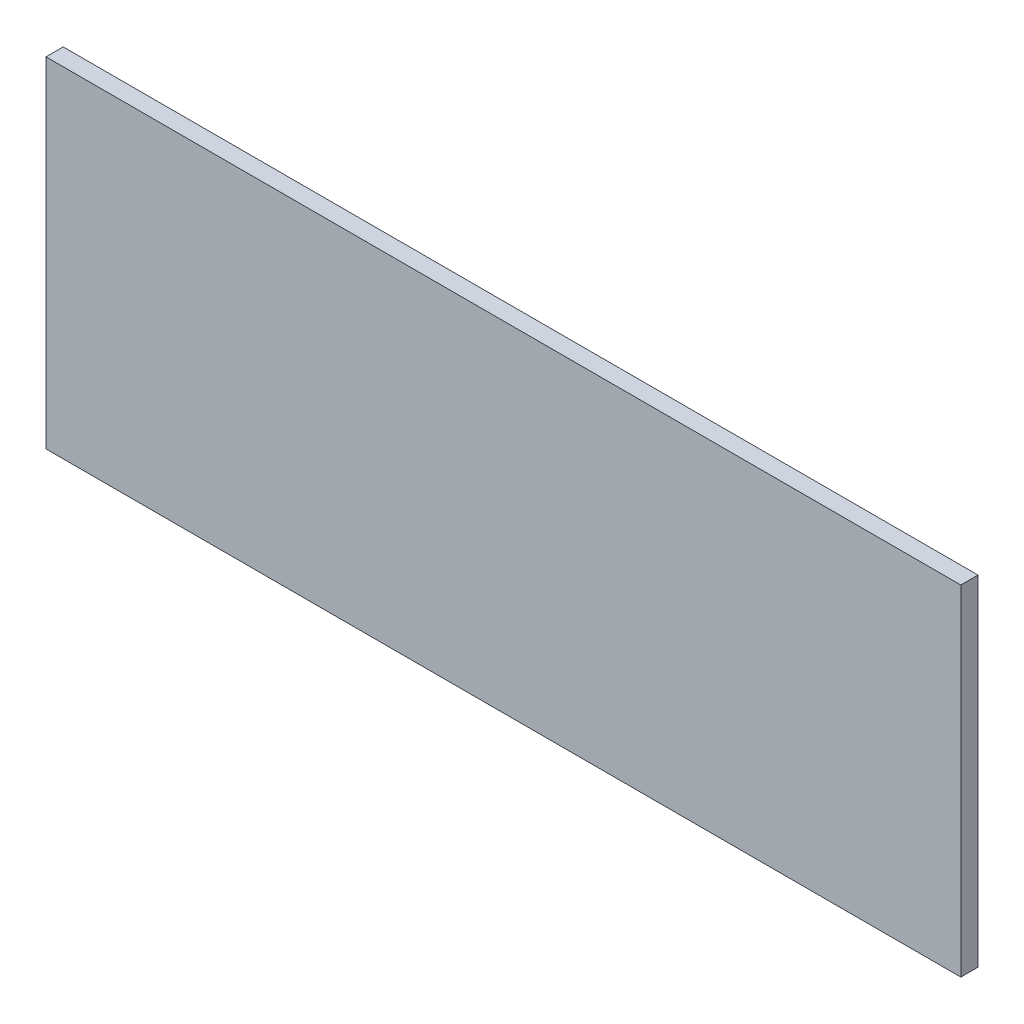
SolidWorks part; units mm, degrees
ref_plane "Plan de face" through (0, 0, 0) normal (0, 0, 1) x (1, 0, 0)
ref_plane "Plan de dessus" through (0, 0, 0) normal (0, 1, 0) x (1, 0, 0)
ref_plane "Plan de droite" through (0, 0, 0) normal (1, 0, 0) x (0, 0, -1)
sketch "Esquisse1" plane through (0, 0, 0) normal (0, 0, 1) x (1, 0, 0)
  line L0 (6, -112.4149) -> (0, -112.4149) construction
  line L1 (6, 6) -> (-313, 6)
  line L2 (6, 6) -> (6, -112.4149)
  line L3 (6, -112.4149) -> (-313, -112.4149)
  line L4 (-313, 6) -> (-313, -112.4149)
  line L5 (-313, 6) -> (-313, 0) construction
extrude "Boss.-Extru.1" add sketch "Esquisse1" along normal blind 6
